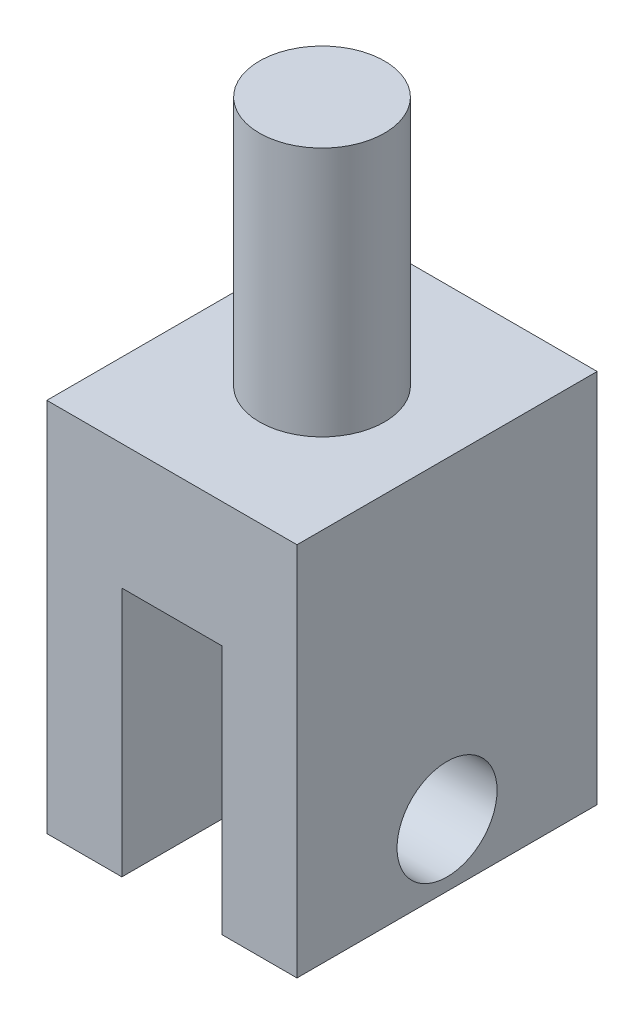
SolidWorks part; units mm, degrees
ref_plane "Front Plane" through (0, 0, 0) normal (0, 0, 1) x (1, 0, 0)
ref_plane "Top Plane" through (0, 0, 0) normal (0, 1, 0) x (1, 0, 0)
ref_plane "Right Plane" through (0, 0, 0) normal (1, 0, 0) x (0, 0, -1)
sketch "Sketch1" plane through (0, 0, 0) normal (0, 1, 0) x (1, 0, 0)
  line L1 (-50, 60) -> (-20, 60)
  line L2 (-50, 60) -> (-50, -60)
  line L3 (-50, -60) -> (-20, -60)
  line L4 (-20, 60) -> (-20, -60)
  line L5 (-50, 60) -> (-20, -60) construction
  line L6 (-50, -60) -> (-20, 60) construction
  line L7 (20, 60) -> (50, 60)
  line L8 (20, 60) -> (20, -60)
  line L9 (20, -60) -> (50, -60)
  line L10 (50, 60) -> (50, -60)
  line L11 (20, 60) -> (50, -60) construction
  line L12 (20, -60) -> (50, 60) construction
  point P0 (-35, 0)
  point P5 (35, 0)
  dimension "D1" = 120
  dimension "D2" = 120
  dimension "D3" = 30
  dimension "D4" = 30
  dimension "D5" = 20
  dimension "D6" = 20
  dimension "D7" = 60
  dimension "D8" = 60
extrude "Boss-Extrude1" add sketch "Sketch1" along normal blind 100
sketch "Sketch2" plane through (50, 0, 0) normal (1, 0, 0) x (0, 0, -1)
  line L0 (-60, 0) -> (60, 0) construction
  circle A0 centre (0, 25) radius 20
  dimension "D1" = 40
  dimension "D2" = 25
extrude "Cut-Extrude1" cut sketch "Sketch2" against normal blind 150
sketch "Sketch3" plane through (0, 100, 0) normal (0, 1, 0) x (1, 0, 0)
  line L1 (-50, 60) -> (50, 60)
  line L2 (-50, 60) -> (-50, -60)
  line L3 (-50, -60) -> (50, -60)
  line L4 (50, 60) -> (50, -60)
extrude "Boss-Extrude2" add sketch "Sketch3" along normal blind 50
sketch "Sketch4" plane through (0, 150, 0) normal (0, 1, 0) x (1, 0, 0)
  circle A0 centre (0, 0) radius 25
  dimension "D1" = 50
extrude "Boss-Extrude3" add sketch "Sketch4" along normal blind 100
